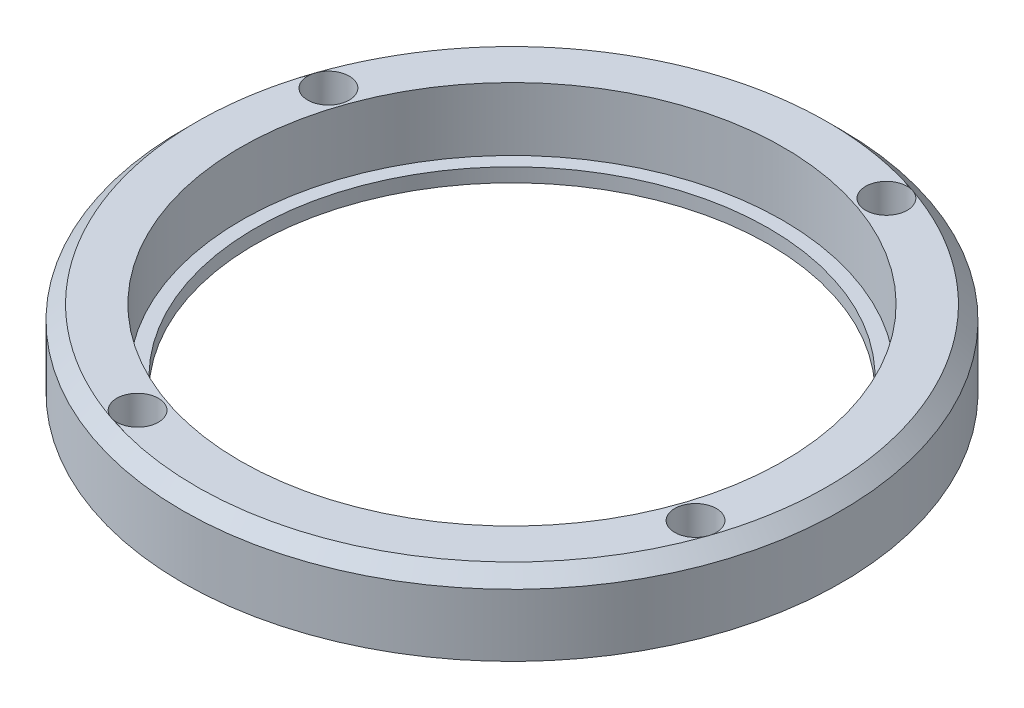
SolidWorks part; units mm, degrees
ref_plane "Front Plane" through (0, 0, 0) normal (0, 0, 1) x (1, 0, 0)
ref_plane "Top Plane" through (0, 0, 0) normal (0, 1, 0) x (1, 0, 0)
ref_plane "Right Plane" through (0, 0, 0) normal (1, 0, 0) x (0, 0, -1)
sketch "Sketch1" plane through (0, 0, 0) normal (0, 1, 0) x (1, 0, 0)
  circle A0 centre (0, 0) radius 47.5
  dimension "D1" = 95
extrude "Boss-Extrude1" add sketch "Sketch1" along normal blind 11 contours A0
sketch "Sketch2" plane through (0, 11, 0) normal (0, 1, 0) x (1, 0, 0)
  circle A0 centre (0, 0) radius 39.15
  dimension "D1" = 78.3
extrude "Cut-Extrude1" cut sketch "Sketch2" against normal through all contours A0
chamfer "Chamfer1" distance 2 angle 45 1 edges at (0, 11, 47.5)
sketch "Sketch5" plane through (0, 11, 0) normal (0, 1, 0) x (1, 0, 0)
  circle A0 centre (13.7564, 40.2121) radius 1.75
  circle A1 centre (40.2121, -13.7564) radius 1.75
  circle A2 centre (-13.7564, -40.2121) radius 1.75
  circle A3 centre (-40.2121, 13.7564) radius 1.75
  dimension "D1" = 3.5
extrude "Cut-Extrude2" cut sketch "Sketch5" against normal through all
sketch "Sketch6" plane through (0, 11, 0) normal (0, 1, 0) x (1, 0, 0)
  circle A0 centre (-13.7564, -40.2121) radius 3
  circle A1 centre (13.7564, 40.2121) radius 3
  circle A2 centre (40.2121, -13.7564) radius 3
  circle A3 centre (-40.2121, 13.7564) radius 3
  dimension "D1" = 6
extrude "Cut-Extrude3" cut sketch "Sketch6" against normal blind 6
sketch "Sketch8" plane through (0, 0, 0) normal (0, -1, 0) x (-1, 0, 0)
  circle A0 centre (0, 0) radius 39
  circle A1 centre (0, 0) radius 37
  dimension "D1" = 78
  dimension "D2" = 74
extrude "Boss-Extrude2" add sketch "Sketch8" against normal blind 2
